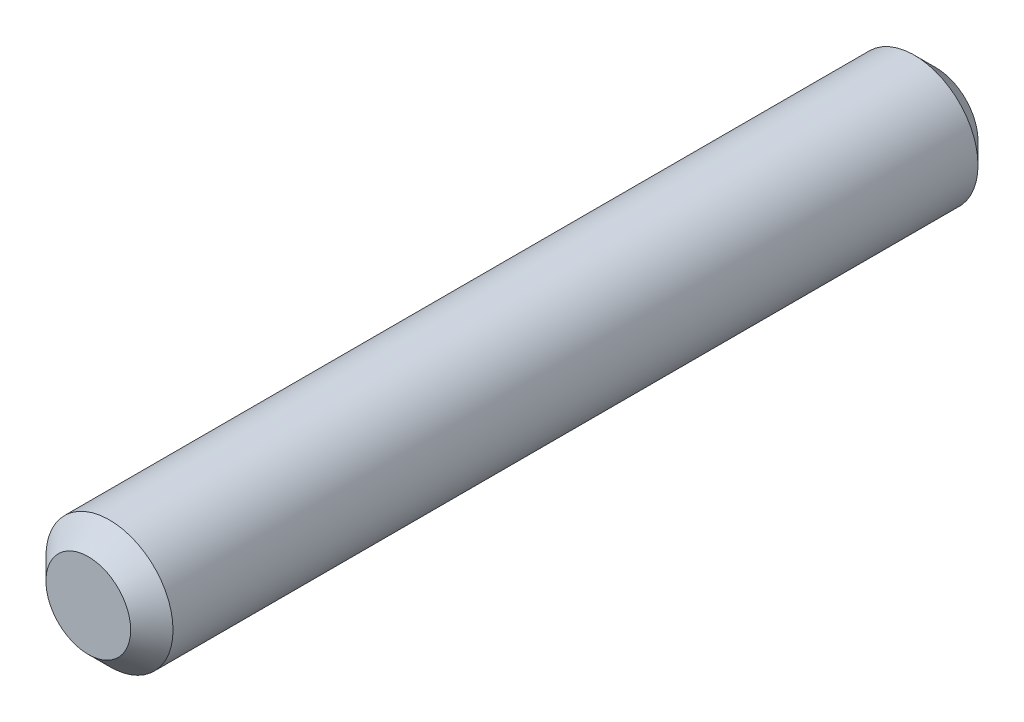
SolidWorks part; units mm, degrees
ref_plane "前视基准面" through (0, 0, 0) normal (0, 0, 1) x (1, 0, 0)
ref_plane "上视基准面" through (0, 0, 0) normal (0, 1, 0) x (1, 0, 0)
ref_plane "右视基准面" through (0, 0, 0) normal (1, 0, 0) x (0, 0, -1)
other "Configuration Table"
sketch "草图1" plane through (0, 0, 0) normal (0, 0, 1) x (1, 0, 0)
  circle A0 centre (0, 0) radius 3
  dimension "D1" = 6
extrude "凸台-拉伸1" add sketch "草图1" along normal mid plane 40
cosmetic thread "装饰螺纹线1" parameters "D1"=20, "D2"=4
cosmetic thread "装饰螺纹线2" parameters "D1"=20, "D2"=4
chamfer "倒角1" distance 1 angle 45 2 edges at (3, 0, -20) (3, 0, 20)
